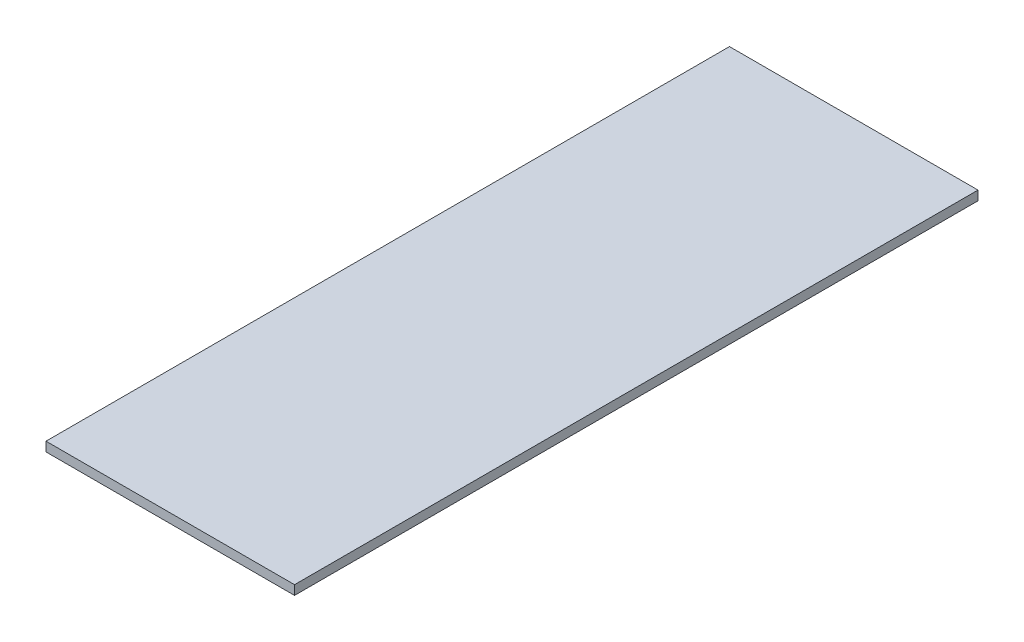
SolidWorks part; units mm, degrees
ref_plane "Front" through (0, 0, 0) normal (0, 0, 1) x (1, 0, 0)
ref_plane "Top" through (0, 0, 0) normal (0, 1, 0) x (1, 0, 0)
ref_plane "Right" through (0, 0, 0) normal (1, 0, 0) x (0, 0, -1)
sketch "Croquis1" plane through (0, 0, 0) normal (0, 1, 0) x (1, 0, 0)
  line L1 (-9.4232, 23.2614) -> (-1.4232, 23.2614)
  line L2 (-9.4232, 23.2614) -> (-9.4232, 1.2614)
  line L3 (-9.4232, 1.2614) -> (-1.4232, 1.2614)
  line L4 (-1.4232, 23.2614) -> (-1.4232, 1.2614)
  dimension "D1" = 8
  dimension "D2" = 22
extrude "Saliente-Extruir1" add sketch "Croquis1" along normal blind 0.3
